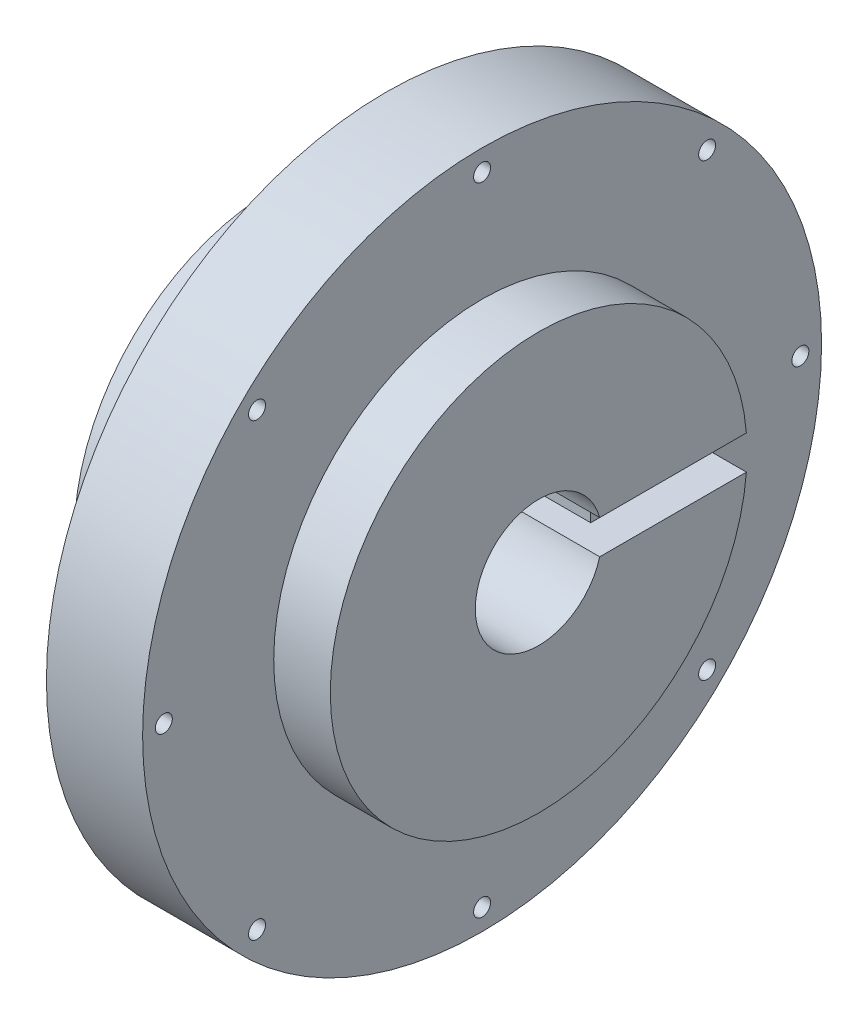
SolidWorks part; units mm, degrees
ref_plane "Front Plane" through (0, 0, 0) normal (0, 0, 1) x (1, 0, 0)
ref_plane "Top Plane" through (0, 0, 0) normal (0, 1, 0) x (1, 0, 0)
ref_plane "Right Plane" through (0, 0, 0) normal (1, 0, 0) x (0, 0, -1)
sketch "Sketch1" plane through (0, 0, 0) normal (0, 0, 1) x (1, 0, 0)
  line L0 (0, 0) -> (0, 60) construction
  line L1 (0, 0) -> (-17, 0)
  line L2 (-17, 0) -> (-17, 25)
  line L3 (-17, 25) -> (-37.05, 25)
  line L4 (-37.05, 25) -> (-37.05, 60)
  line L5 (-37.05, 60) -> (0, 60)
  line L6 (0, 60) -> (0, 0)
  dimension "D1" = 60
  dimension "D2" = 35
  dimension "D3" = 17
  dimension "D4" = 37.05
revolve "Revolve1" add sketch "Sketch1" angle 360 about L5
sketch "upper cirlce" plane through (0, 0, 0) normal (1, 0, 0) x (0, 0, -1)
  circle A0 centre (0, 60) radius 36.83
  dimension "D1" = 73.66
extrude "upper cirlce " add sketch "upper cirlce" along normal blind 10
sketch "ref hex" plane through (0, 0, 0) normal (1, 0, 0) x (0, 0, -1)
  line L1 (0, 109.5) -> (-42.8683, 84.75)
  line L2 (-42.8683, 84.75) -> (-42.8683, 35.25)
  line L3 (-42.8683, 35.25) -> (0, 10.5)
  line L4 (0, 10.5) -> (42.8683, 35.25)
  line L5 (42.8683, 35.25) -> (42.8683, 84.75)
  line L6 (42.8683, 84.75) -> (0, 109.5)
  circle A0 centre (0, 60) radius 42.8683 construction
  dimension "D1" = 49.5
sketch "m3 holes" plane through (0, 0, 0) normal (1, 0, 0) x (0, 0, -1)
  circle A0 centre (-42.8683, 84.75) radius 1.4
  circle A1 centre (-42.8683, 35.25) radius 1.4
  circle A2 centre (0, 10.5) radius 1.4
  circle A3 centre (42.8683, 35.25) radius 1.4
  circle A4 centre (42.8683, 84.75) radius 1.4
  circle A5 centre (0, 109.5) radius 1.4
  dimension "D1" = 2.8
  dimension "D2" = 2.8
  dimension "D3" = 2.8
  dimension "D4" = 2.8
  dimension "D5" = 2.8
  dimension "D6" = 2.8
extrude "holes" [suppressed] cut sketch "m3 holes" against normal blind 16
sketch "pin ref" plane through (-37.05, 0, 0) normal (-1, 0, 0) x (0, 0, 1)
  line L1 (0, 60) -> (18.56, 60)
  line L2 (0, 60) -> (0, 78.56)
  line L3 (0, 78.56) -> (18.56, 78.56)
  line L4 (18.56, 60) -> (18.56, 78.56)
  line L5 (0, 60) -> (18.56, 60)
  line L6 (0, 60) -> (0, 41.44)
  line L7 (0, 41.44) -> (18.56, 41.44)
  line L8 (18.56, 60) -> (18.56, 41.44)
  line L9 (0, 60) -> (-18.56, 60)
  line L10 (0, 60) -> (0, 41.44)
  line L11 (0, 41.44) -> (-18.56, 41.44)
  line L12 (-18.56, 60) -> (-18.56, 41.44)
  line L13 (0, 60) -> (-18.56, 60)
  line L14 (0, 60) -> (0, 78.56)
  line L15 (0, 78.56) -> (-18.56, 78.56)
  line L16 (-18.56, 60) -> (-18.56, 78.56)
  dimension "D1" = 18.56
  dimension "D2" = 18.56
  dimension "D3" = 18.56
sketch "pin sketch" plane through (-37.05, 0, 0) normal (-1, 0, 0) x (0, 0, 1)
  circle A0 centre (-18.56, 78.56) radius 2
  circle A1 centre (18.56, 78.56) radius 2
  circle A2 centre (18.56, 41.44) radius 2
  circle A3 centre (-18.56, 41.44) radius 2
  dimension "D1" = 4
  dimension "4" = 4
  dimension "D2" = 4
  dimension "D3" = 4
sketch "Sketch2" plane through (0, 0, 0) normal (1, 0, 0) x (0, 0, -1)
  circle A3 centre (0, 116.25) radius 1.5
  dimension "D2" = 3
extrude "Cut-Extrude1" cut sketch "Sketch2" against normal through all both and the other way through all
pattern_circular "CirPattern1" count 8 over 360 about axis through (0, 60, 0) along (1, 0, 0) of "Cut-Extrude1"
extrude "Cut-Extrude2" cut sketch "pin sketch" against normal blind 10
sketch "Sketch3" plane through (10, 0, 0) normal (1, 0, 0) x (0, 0, -1)
  circle A0 centre (0, 60) radius 11.2
extrude "Cut-Extrude3" cut sketch "Sketch3" against normal blind 29
sketch "Sketch4" plane through (-19, 0, 0) normal (1, 0, 0) x (0, 0, -1)
  line L0 (0, 60) -> (18.56, 60) construction
  line L1 (7.2, 63) -> (15.2, 63)
  line L2 (7.2, 63) -> (7.2, 57)
  line L3 (7.2, 57) -> (15.2, 57)
  line L4 (15.2, 63) -> (15.2, 57)
  line L5 (7.2, 63) -> (15.2, 57) construction
  line L6 (7.2, 57) -> (15.2, 63) construction
  circle A0 centre (0, 60) radius 11.2 construction
  point P0 (11.2, 60)
  dimension "D1" = 6
  dimension "D2" = 8
extrude "Cut-Extrude4" cut sketch "Sketch4" along normal blind 70
sketch "Sketch6" plane through (10, 0, 0) normal (1, 0, 0) x (0, 0, -1)
  line L5 (15.2, 63) -> (37.5465, 63)
  line L6 (15.2, 63) -> (15.2, 57)
  line L7 (15.2, 57) -> (37.5465, 57)
  line L8 (37.5465, 63) -> (37.5465, 57)
extrude "Cut-Extrude5" cut sketch "Sketch6" against normal blind 6
sketch "Sketch7" plane through (-19, 0, 0) normal (1, 0, 0) x (0, 0, -1)
  line L1 (15.2, 63) -> (-1.9896, 63)
  line L2 (15.2, 63) -> (15.2, 57)
  line L3 (15.2, 57) -> (-1.9896, 57)
  line L4 (-1.9896, 63) -> (-1.9896, 57)
extrude "Cut-Extrude6" cut sketch "Sketch7" against normal blind 4
